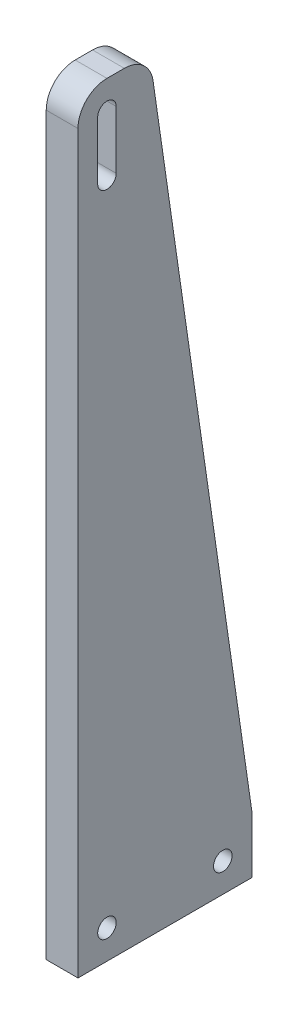
SolidWorks part; units mm, degrees
ref_plane "Front Plane" through (0, 0, 0) normal (0, 0, 1) x (1, 0, 0)
ref_plane "Top Plane" through (0, 0, 0) normal (0, 1, 0) x (1, 0, 0)
ref_plane "Right Plane" through (0, 0, 0) normal (1, 0, 0) x (0, 0, -1)
sketch "Sketch1" plane through (0, 0, 0) normal (1, 0, 0) x (0, 0, -1)
  line L0 (0, 0) -> (30, 0)
  line L1 (30, 0) -> (30, 10)
  line L2 (5, 132) -> (8, 132)
  line L3 (0, 0) -> (0, 127)
  line L4 (5, 117) -> (5, 127) construction
  line L5 (3.4, 117) -> (3.4, 127)
  line L6 (6.6, 117) -> (6.6, 127)
  line L7 (30, 10) -> (0, 10) construction
  line L8 (15, 10) -> (15, 0) construction
  line L9 (5, 5) -> (25, 5) construction
  line L10 (30, 10) -> (12.9484, 127.7168)
  arc A0 (0, 127) -> (5, 132) centre (5, 127) cw
  arc A1 (3.4, 117) -> (6.6, 117) centre (5, 117) ccw
  arc A2 (6.6, 127) -> (3.4, 127) centre (5, 127) ccw
  circle A3 centre (5, 5) radius 1.6
  circle A4 centre (25, 5) radius 1.6
  arc A5 (8, 132) -> (12.9484, 127.7168) centre (8, 127) cw
  point P9 (5, 122)
  point P20 (15, 5)
  point P25 (12.1036, 127.5112)
  point P26 (9.7439, 129.6815)
  point P27 (12.684, 127)
  dimension "D7" = 3.2
  dimension "D1" = 10
  dimension "D2" = 30
  dimension "D3" = 10
  dimension "D4" = 3.2
  dimension "D5" = 122
  dimension "D6" = 5
  dimension "D8" = 20
  dimension "D9" = 3
extrude "Boss-Extrude1" add sketch "Sketch1" along normal blind 5.4864
